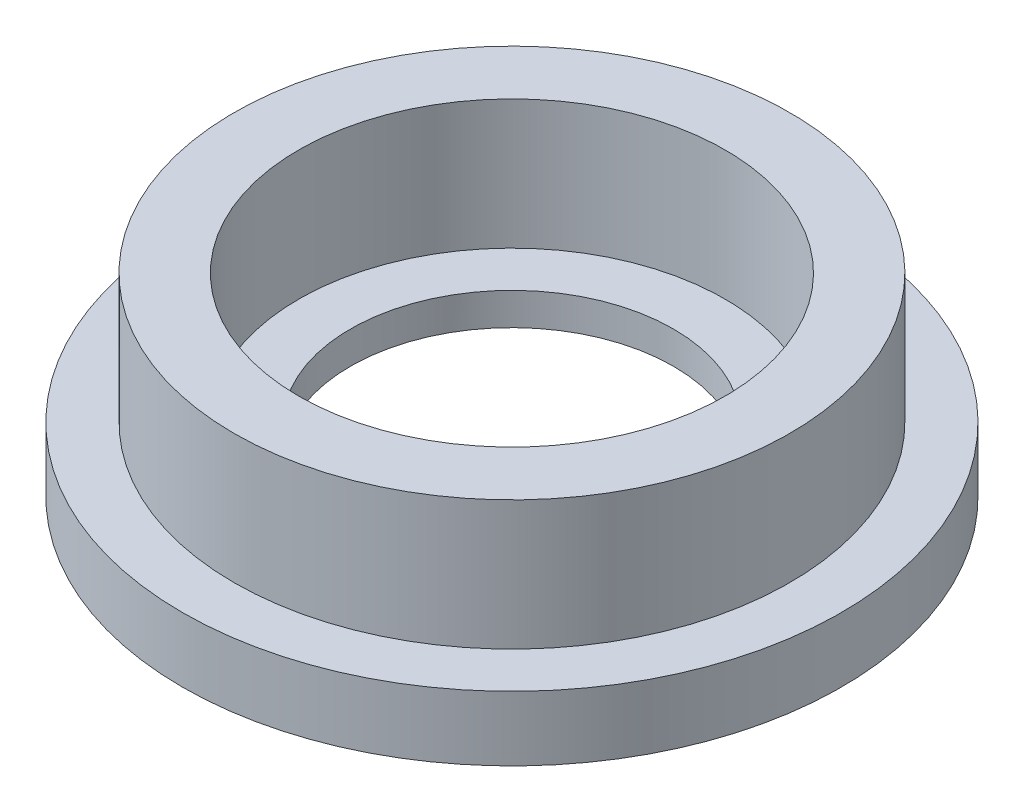
SolidWorks part; units mm, degrees
ref_plane "Front Plane" through (0, 0, 0) normal (0, 0, 1) x (1, 0, 0)
ref_plane "Top Plane" through (0, 0, 0) normal (0, 1, 0) x (1, 0, 0)
ref_plane "Right Plane" through (0, 0, 0) normal (1, 0, 0) x (0, 0, -1)
sketch "Sketch1" plane through (0, 0, 0) normal (0, 1, 0) x (1, 0, 0)
  circle A0 centre (0, 0) radius 5.1
  dimension "D1" = 10.2
extrude "Boss-Extrude1" add sketch "Sketch1" along normal blind 1 contours A0
sketch "Sketch2" plane through (0, 1, 0) normal (0, 1, 0) x (1, 0, 0)
  circle A0 centre (0, 0) radius 4.3
  circle A1 centre (0, 0) radius 3.3
  dimension "D1" = 8.6
  dimension "D2" = 6.6
extrude "Boss-Extrude2" add sketch "Sketch2" along normal blind 2
sketch "Sketch3" plane through (0, 0, 0) normal (0, -1, 0) x (1, 0, 0)
  circle A0 centre (0, 0) radius 2.5
  dimension "D1" = 5
extrude "Cut-Extrude1" cut sketch "Sketch3" against normal blind 2
sketch "Sketch4" plane through (0, 0, 0) normal (0, -1, 0) x (1, 0, 0)
  circle A0 centre (0, 0) radius 3.3
  dimension "D1" = 6.6
extrude "Cut-Extrude2" cut sketch "Sketch4" against normal blind 0.5
